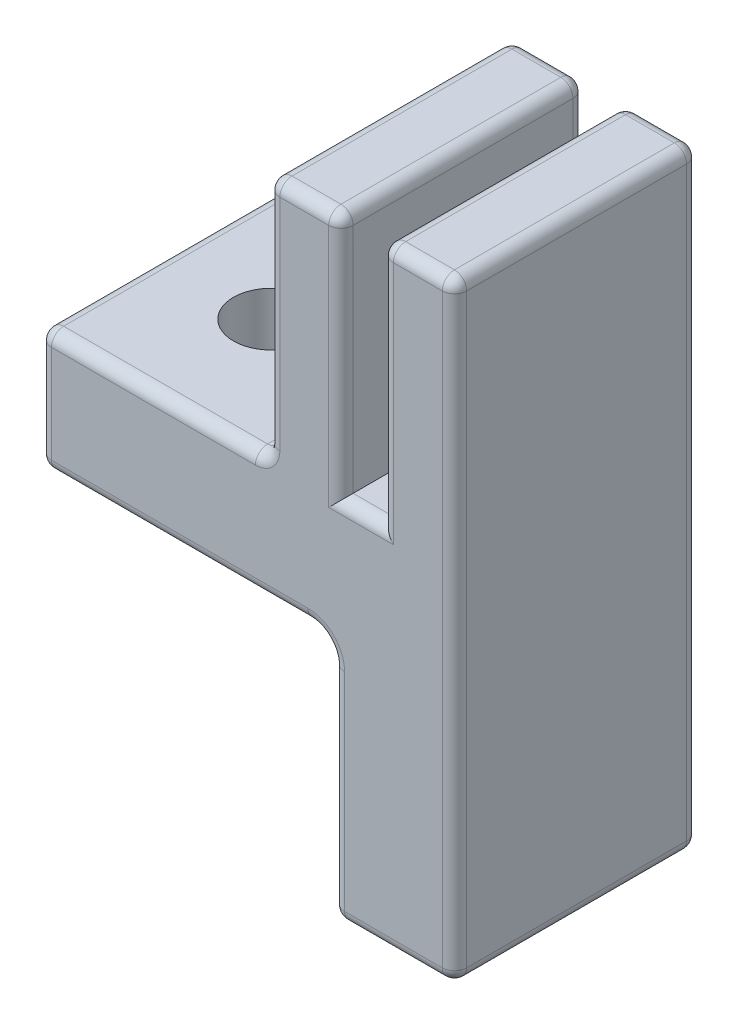
SolidWorks part; units mm, degrees
ref_plane "Front Plane" through (0, 0, 0) normal (0, 0, 1) x (1, 0, 0)
ref_plane "Top Plane" through (0, 0, 0) normal (0, 1, 0) x (1, 0, 0)
ref_plane "Right Plane" through (0, 0, 0) normal (1, 0, 0) x (0, 0, -1)
sketch "Sketch1" plane through (0, 0, 0) normal (0, 0, 1) x (1, 0, 0)
  line L0 (-6, 10) -> (11, 10)
  line L3 (-6, 5) -> (6, 5)
  line L4 (6, -5) -> (6, 5)
  line L5 (-5.4321, -4.5268) -> (6, 5) construction
  line L6 (-6, 5) -> (6, -5) construction
  line L7 (11, -5) -> (11, 10)
  line L8 (8, 10) -> (8, 5) construction
  line L9 (8, 15) -> (7.175, 15) construction
  line L10 (8, 10) -> (11, 10)
  line L11 (8, 10) -> (8, 20)
  line L12 (8, 20) -> (11, 20)
  line L13 (11, 10) -> (11, 20)
  line L14 (7.175, 8.2112) -> (7.175, 21.7888) construction
  line L15 (6.35, 20) -> (3.35, 20)
  line L16 (3.35, 10) -> (3.35, 20)
  line L17 (6.35, 10) -> (3.35, 10)
  line L18 (6.35, 10) -> (6.35, 20)
  line L19 (8, 5) -> (6, 5) construction
  line L20 (6, 0) -> (-0.5, 0) construction
  line L21 (-6, 10) -> (-6, 5)
  line L22 (6, -5) -> (11, -5)
  point P0 (0, 0)
  point P17 (7.175, 15)
  dimension "D1" = 12
  dimension "D2" = 10
  dimension "D4" = 0.825
  dimension "D5" = 2
  dimension "D6" = 6.5
  dimension "D7" = 10
  dimension "D3" = 5
extrude "Boss-Extrude1" add sketch "Sketch1" along normal blind 10 contours L4 L22 L7 L0 L21 L3 | L0 L18 L15 L16 | L0 L13 L12 L11
sketch "Sketch3" plane through (0, 5, 0) normal (0, -1, 0) x (1, 0, 0)
  line L0 (6, 5) -> (-1.5, 5) construction
  line L1 (6, 10) -> (6, 0) construction
  circle A0 centre (-1.5, 5) radius 1.55
  dimension "D2" = 3.1
  dimension "D1" = 7.5
extrude "Cut-Extrude1" cut sketch "Sketch3" against normal blind 10 contours A0
fillet "Fillet1" radius 1 1 edges at (6, 5, 5)
fillet "Fillet2" radius 0.5 35 edges at (8.5, -5, 10) (-0.5, 5, 0) (-6, 7.5, 0) (11, 7.5, 10) (-1.325, 10, 0) (3.35, 15, 0) (4.85, 20, 0) (6.35, 15, 0) (7.175, 10, 0) (8, 15, 0) (9.5, 20, 0) (11, 7.5, 0) (8.5, -5, 0) (6, -0.5, 0) (9.5, 20, 10) (-6, 5, 5) (-6, 10, 5) (3.35, 10, 5) (3.35, 20, 5) (6.35, 20, 5) (8, 20, 5) (11, 20, 5) (11, -5, 5) (6, -5, 5) (8, 15, 10) (7.175, 10, 10) (6.35, 15, 10) (4.85, 20, 10) (5.7071, 4.7071, 0) (5.7071, 4.7071, 10) (3.35, 15, 10) (6, -0.5, 10) (-1.325, 10, 10) (-6, 7.5, 10) (-0.5, 5, 10)
